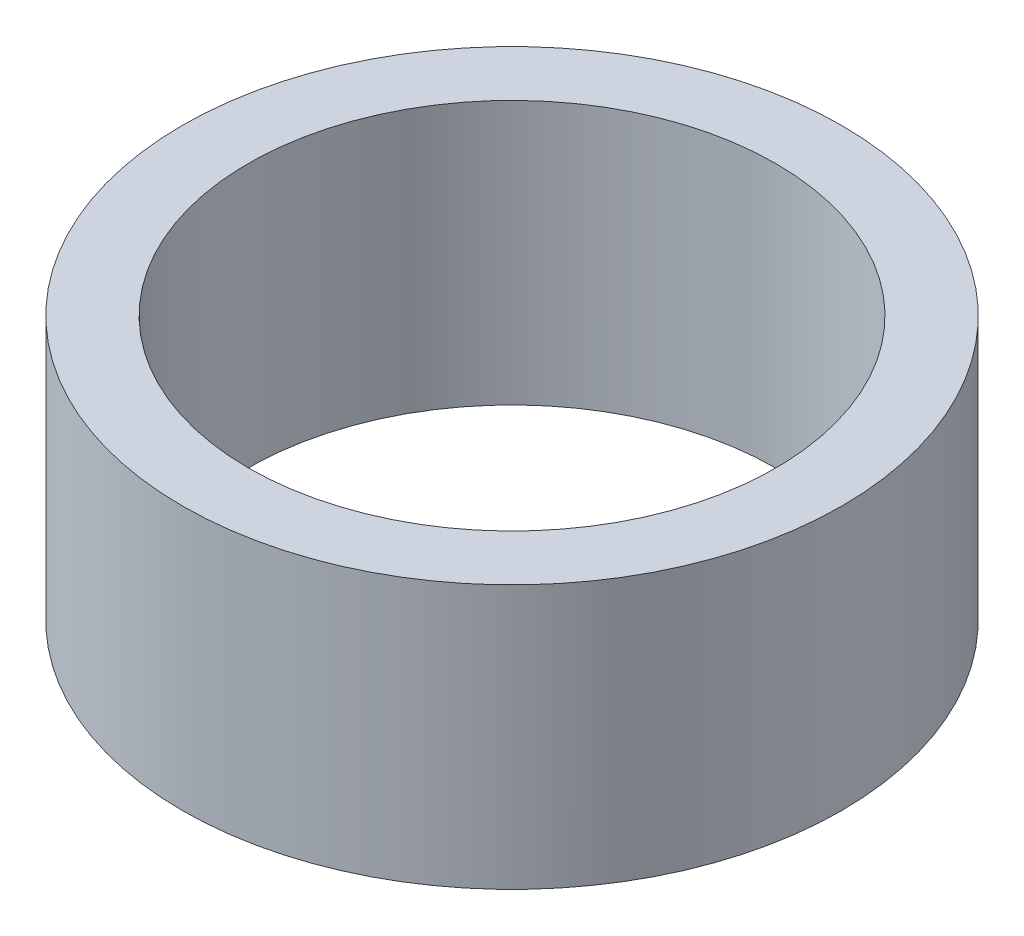
SolidWorks part; units mm, degrees
ref_plane "Plan1" through (0, 0, 0) normal (0, 0, 1) x (1, 0, 0)
ref_plane "Plan2" through (0, 0, 0) normal (0, 1, 0) x (1, 0, 0)
ref_plane "Plan3" through (0, 0, 0) normal (1, 0, 0) x (0, 0, -1)
ref_plane "Plan4" through (0.0771, 595.6937, -0.1172) normal (0.0001, 1, -0.0002) x (-1, 0.0001, 0)
sketch "Esquisse1" plane through (0.0771, 595.6937, -0.1172) normal (0.0001, 1, -0.0002) x (-1, 0.0001, 0)
  circle A0 centre (-2143.7061, 669.1106) radius 4
  circle A1 centre (-2143.7061, 669.1106) radius 5
  dimension "D1" = 10
  dimension "D2" = 8
extrude "Base-Extrusion" add sketch "Esquisse1" against normal blind 4
